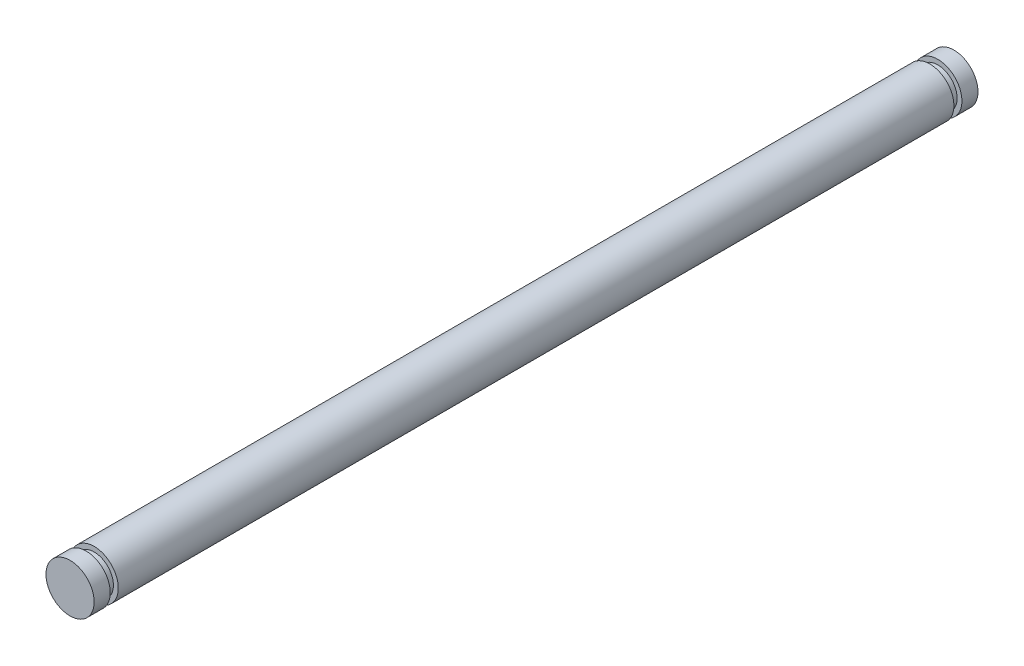
SolidWorks part; units mm, degrees
material "Cast Alloy Steel"
ref_plane "Front" through (0, 0, 0) normal (0, 0, 1) x (1, 0, 0)
ref_plane "Top" through (0, 0, 0) normal (0, 1, 0) x (1, 0, 0)
ref_plane "Right" through (0, 0, 0) normal (1, 0, 0) x (0, 0, -1)
sketch "Sketch1" plane through (0, 0, 0) normal (0, 0, 1) x (1, 0, 0)
  circle A0 centre (0, 0) radius 1.5
  dimension "D1" = 3
extrude "Boss-Extrude1" add sketch "Sketch1" along normal blind 55
sketch "Sketch2" plane through (0, 0, 0) normal (0, 1, 0) x (1, 0, 0)
  line L0 (0, 0) -> (0, -8.3218) construction
  line L1 (1.5, 0) -> (-1.5, 0) construction
  line L2 (-1.2, -1) -> (-4.368, -1)
  line L3 (-1.2, -1) -> (-1.2, -1.5)
  line L4 (-1.2, -1.5) -> (-4.368, -1.5)
  line L5 (-4.368, -1) -> (-4.368, -1.5)
  line L6 (-1.5, 0) -> (-1.5, -55) construction
  dimension "D1" = 0.5
  dimension "D2" = 1
  dimension "D3" = 0.3
revolve "Cut-Revolve1" cut sketch "Sketch2" angle 360 about L0
ref_plane "Plane1" through (0, 0, 27.5) normal (0, 0, 1) x (1, 0, 0)
mirror "Mirror1" about plane through (0, 0, 27.5) normal (0, 0, 1) of "Cut-Revolve1"
